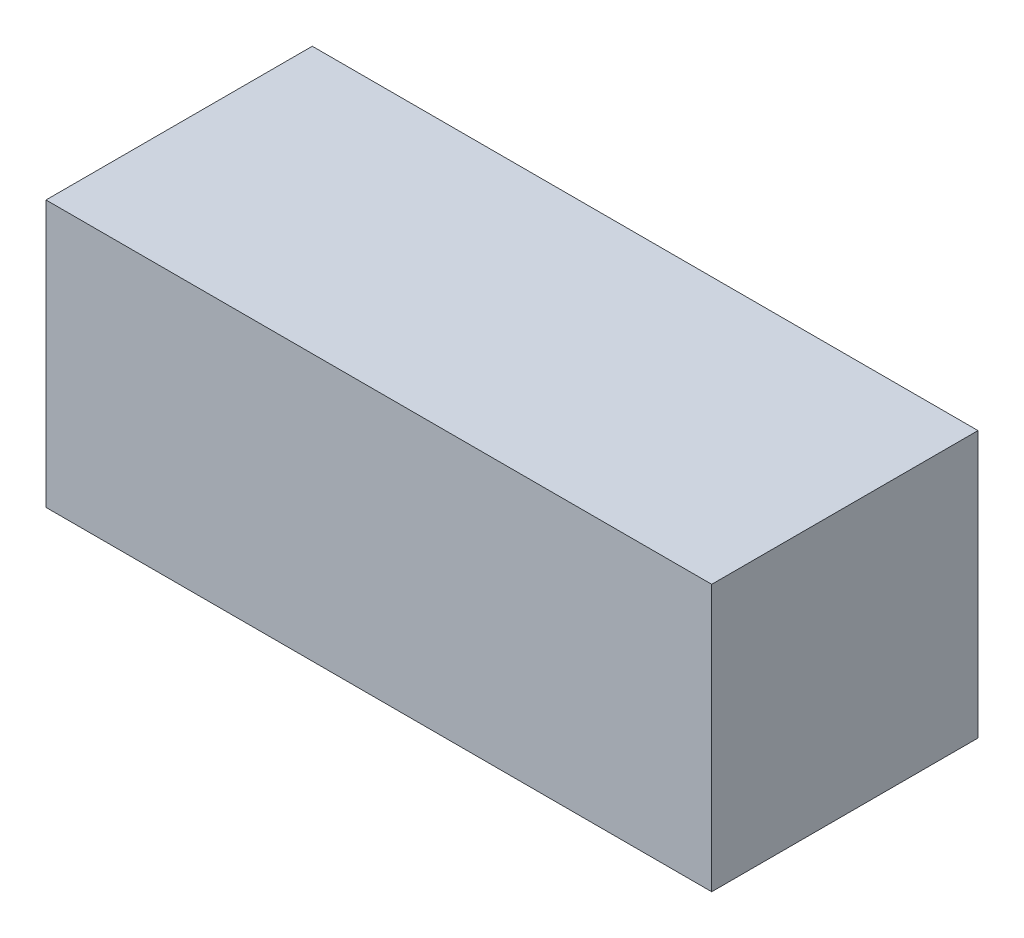
SolidWorks part; units mm, degrees
ref_plane "前视基准面" through (0, 0, 0) normal (0, 0, 1) x (1, 0, 0)
ref_plane "上视基准面" through (0, 0, 0) normal (0, 1, 0) x (1, 0, 0)
ref_plane "右视基准面" through (0, 0, 0) normal (1, 0, 0) x (0, 0, -1)
other "Configuration Table"
sketch "草图1" plane through (0, 0, 0) normal (1, 0, 0) x (0, 0, -1)
  line L1 (-39.295, 55.0358) -> (60.705, 55.0358)
  line L2 (-39.295, 55.0358) -> (-39.295, -44.9642)
  line L3 (-39.295, -44.9642) -> (60.705, -44.9642)
  line L4 (60.705, 55.0358) -> (60.705, -44.9642)
  dimension "D1" = 100
  dimension "D2" = 100
extrude "凸台-拉伸1" add sketch "草图1" along normal blind 250
